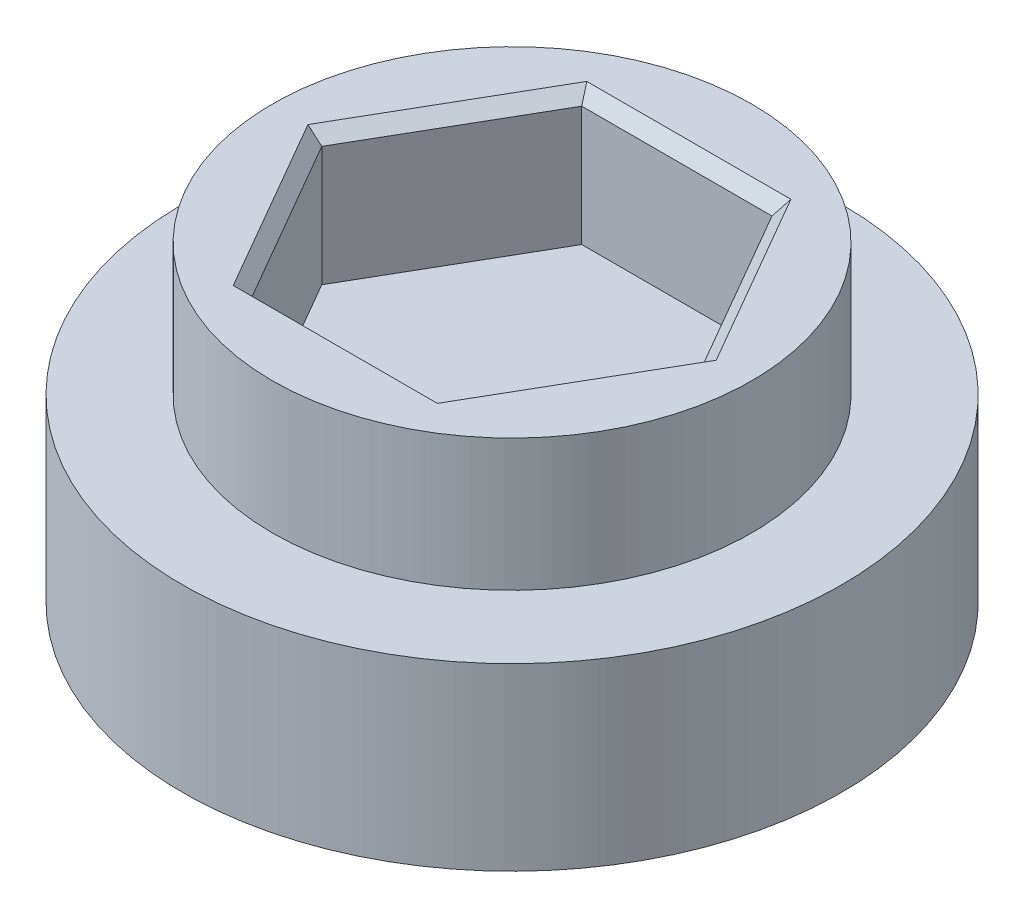
SolidWorks part; units mm, degrees
ref_plane "Płaszczyzna przednia" through (0, 0, 0) normal (0, 0, 1) x (1, 0, 0)
ref_plane "Płaszczyzna górna" through (0, 0, 0) normal (0, 1, 0) x (1, 0, 0)
ref_plane "Płaszczyzna prawa" through (0, 0, 0) normal (1, 0, 0) x (0, 0, -1)
sketch "Szkic1" plane through (0, 0, 0) normal (0, 1, 0) x (1, 0, 0)
  line L6 (-15.8771, 27.5) -> (15.8771, 27.5)
  line L7 (15.8771, 27.5) -> (31.7543, 0)
  line L8 (31.7543, 0) -> (15.8771, -27.5)
  line L9 (15.8771, -27.5) -> (-15.8771, -27.5)
  line L10 (-15.8771, -27.5) -> (-31.7543, 0)
  line L11 (-31.7543, 0) -> (-15.8771, 27.5)
  circle A0 centre (0, 0) radius 40
  point P11 (0, 0)
  dimension "D1" = 80
extrude "Dodanie-wyciągnięcie1" add sketch "Szkic1" along normal blind 22
chamfer "Sfazowanie1" distance 2 angle 45 6 edges at (-23.8157, 22, 13.75) (0, 22, 27.5) (23.8157, 22, 13.75) (23.8157, 22, -13.75) (0, 22, -27.5) (-23.8157, 22, -13.75)
sketch "Szkic2" plane through (0, 0, 0) normal (0, -1, 0) x (1, 0, 0)
  circle A0 centre (0, 0) radius 55
  dimension "D1" = 110
extrude "Dodanie-wyciągnięcie2" add sketch "Szkic2" along normal blind 30
